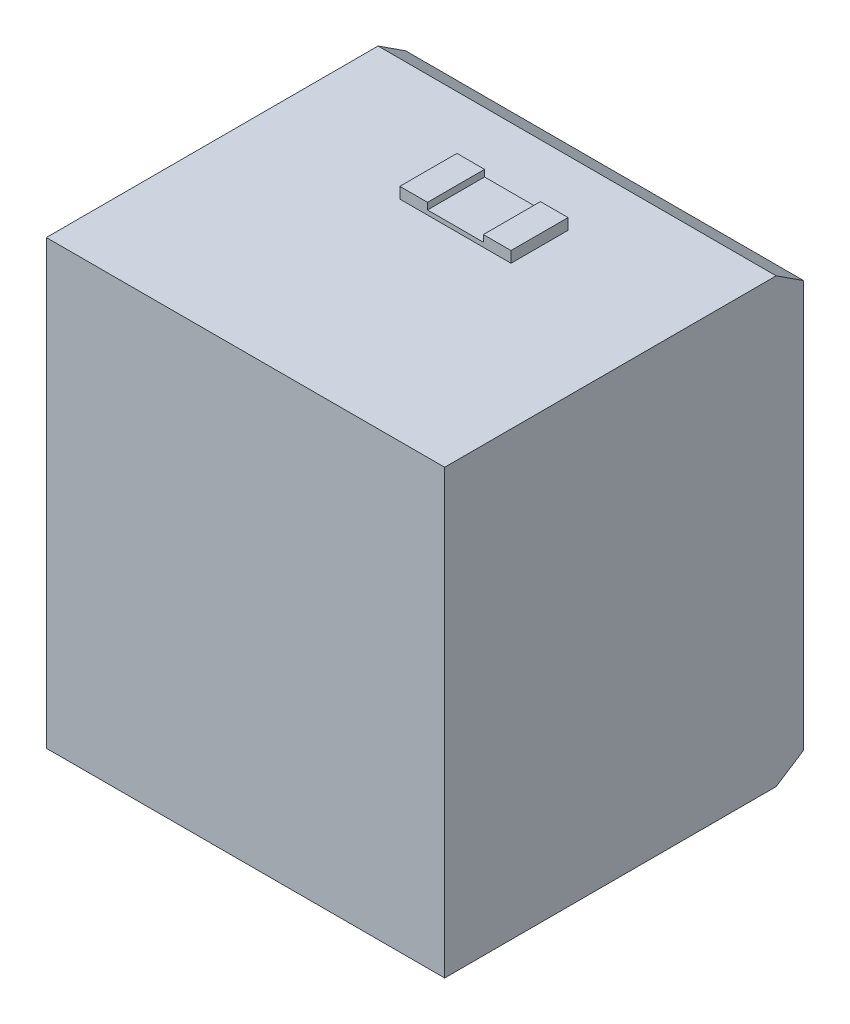
SolidWorks part; units mm, degrees
ref_plane "Front Plane" through (0, 0, 0) normal (0, 0, 1) x (1, 0, 0)
ref_plane "Top Plane" through (0, 0, 0) normal (0, 1, 0) x (1, 0, 0)
ref_plane "Right Plane" through (0, 0, 0) normal (1, 0, 0) x (0, 0, -1)
sketch "Sketch1" plane through (0, 0, 0) normal (0, 1, 0) x (1, 0, 0)
  line L0 (-457.2, 0) -> (457.2, 0) construction
  line L1 (-457.2, -381) -> (-457.2, 381)
  line L2 (0, 1430.6363) -> (0, -1430.6363) construction
  line L3 (-457.2, 381) -> (457.2, 380.492)
  line L4 (457.2, 380.492) -> (457.2, -380.492)
  line L5 (-431.8, -355.092) -> (-431.8, 355.092)
  line L6 (431.8, -355.092) -> (431.8, 355.092)
  line L7 (-431.8, 380.617) -> (-431.8, 355.217) construction
  line L8 (-431.8, 355.217) -> (431.8, 355.092)
  line L9 (-431.8, -355.217) -> (431.8, -355.092)
  line L10 (-457.2, -381) -> (457.2, -380.492)
  point P4 (0, 0)
  point P9 (0, 0)
  point P17 (-431.8, 0)
  point P19 (431.8, 0)
  dimension "D1" = 914.4
  dimension "D2" = 381
  dimension "D3" = 25.4
  dimension "D4" = 25.4
  dimension "D5" = 355.092
  dimension "D6" = 25.4
  dimension "D7" = 355.092
  dimension "D8" = 380.492
extrude "Boss-Extrude1" add sketch "Sketch1" along normal blind 1016
sketch "Sketch2" plane through (0.2115, 0, -380.7459) normal (0.0006, 0, -1) x (-1, 0, -0.0006)
  line L0 (0.2115, 1016) -> (0, 0) construction
  line L2 (-417.3485, 994.2582) -> (417.5615, 994.2582)
  line L3 (-417.3485, 994.2582) -> (-417.3485, 28.9094)
  line L12 (-417.3485, 28.9094) -> (417.5615, 28.9094)
  line L13 (417.5615, 994.2582) -> (417.5615, 28.9094)
  line L14 (-417.3485, 994.2582) -> (417.5615, 28.9094) construction
  line L15 (-417.3485, 28.9094) -> (417.5615, 994.2582) construction
  point P7 (0.1065, 511.5838)
extrude "Cut-Extrude1" cut sketch "Sketch2" against normal blind 723.9
sketch "Sketch3" plane through (-0.1906, 0, 343.154) normal (0.0006, 0, -1) x (-1, 0, -0.0006)
  circle A0 centre (-351.2534, 946.4694) radius 38.1
  dimension "D1" = 76.2
extrude "Boss-Extrude2" add sketch "Sketch3" along normal blind 723.9
sketch "Sketch4" plane through (0.2115, 0, -380.7459) normal (0.0006, 0, -1) x (-1, 0, -0.0006)
  circle A0 centre (-354.2875, 946.2333) radius 21.8245
extrude "Boss-Extrude3" add sketch "Sketch4" along normal blind 3.556
pattern_linear "LPattern4" count 7 spacing 114.3 along (-1, 0, -0.0006) count 9 spacing 104.14 along (0, -1, 0) of "Boss-Extrude2", "Boss-Extrude3"
sketch "Sketch5" plane through (-457.2, 0, 0) normal (-1, 0, 0) x (0, 0, 1)
  line L0 (-381, 0) -> (-444.109, 41.0183)
  line L1 (-471.9035, 508) -> (-205.3538, 508) construction
  line L2 (-381, 1016) -> (-444.109, 974.9817)
  line L3 (-444.109, 41.0183) -> (-444.109, 974.9817)
  line L4 (-381, 0) -> (381, 0)
  line L5 (381, 0) -> (381, 1016)
  line L6 (381, 1016) -> (-381, 1016)
  line L7 (-381, 1016) -> (-381, 0)
  line L11 (-381, 508) -> (-381, 0)
  line L12 (-355.209, 0) -> (-355.209, 1016)
  line L13 (381, 0) -> (-381, 0) construction
  line L14 (381, 1016) -> (-381, 1016) construction
  line L15 (-381, 0) -> (-355.209, 0)
  line L17 (-381, 1016) -> (-355.209, 1016)
  line M7 (-381, 0) -> (381, 0)
  line M9 (381, 1016) -> (-381, 1016)
  line M10 (-381, 1016) -> (-381, 0)
  dimension "D2" = 88.9
  dimension "D1" = 0
extrude "Boss-Extrude5" add sketch "Sketch5" against normal up to surface (914.4 mm away) contours L1 L12 M10 M7 | L1 L12 M10 M9 | L1 L3 L0 M10 | L3 L1 L2 M10 up to face at (457.2, 508, 0)
sketch "Sketch6" plane through (0, 1016, 0) normal (0, 1, 0) x (1, 0, 0)
  line L1 (-127.6597, 232.5093) -> (127.6597, 232.5093)
  line L2 (-127.6597, 232.5093) -> (-127.6597, 101.4518)
  line L3 (-127.6597, 101.4518) -> (127.6597, 101.4518)
  line L4 (127.6597, 232.5093) -> (127.6597, 101.4518)
  line L5 (-127.6597, 232.5093) -> (127.6597, 101.4518) construction
  line L6 (-127.6597, 101.4518) -> (127.6597, 232.5093) construction
  point P0 (0, 166.9805)
extrude "Boss-Extrude6" add sketch "Sketch6" along normal blind 10.16
sketch "Sketch7" plane through (0, 1026.16, 0) normal (0, 1, 0) x (1, 0, 0)
  line L0 (-64.1597, 232.5093) -> (-64.1597, 101.4518)
  line L1 (64.1597, 232.5093) -> (64.1597, 101.4518)
  line L2 (-64.1597, 232.5093) -> (-127.6597, 232.5093)
  line L3 (64.1597, 101.4518) -> (127.6597, 101.4518)
  line L4 (127.6597, 101.4518) -> (127.6597, 232.5093)
  line L5 (127.6597, 232.5093) -> (-127.6597, 232.5093)
  line L6 (-127.6597, 232.5093) -> (-127.6597, 101.4518)
  line L7 (-127.6597, 101.4518) -> (127.6597, 101.4518)
  line L8 (127.6597, 101.4518) -> (127.6597, 232.5093)
  line L9 (127.6597, 232.5093) -> (64.1597, 232.5093)
  line L10 (-127.6597, 232.5093) -> (-127.6597, 101.4518)
  line L11 (-127.6597, 101.4518) -> (-64.1597, 101.4518)
  dimension "D2" = 63.5
  dimension "D3" = 63.5
  dimension "D1" = 0
extrude "Boss-Extrude7" add sketch "Sketch7" along normal blind 15.24
